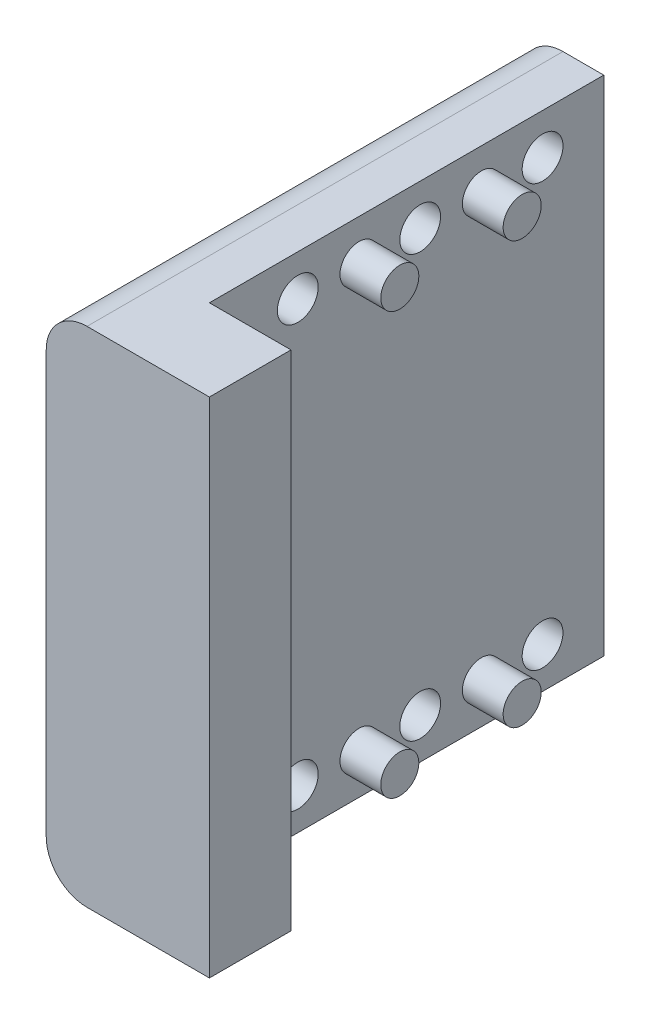
SolidWorks part; units mm, degrees
ref_plane "Front Plane" through (0, 0, 0) normal (0, 0, 1) x (1, 0, 0)
ref_plane "Top Plane" through (0, 0, 0) normal (0, 1, 0) x (1, 0, 0)
ref_plane "Right Plane" through (0, 0, 0) normal (1, 0, 0) x (0, 0, -1)
sketch "Sketch1" plane through (0, 0, 0) normal (0, 1, 0) x (1, 0, 0)
  line L0 (-15.8302, 22.3908) -> (-15.8302, -12.6092)
  line L1 (-15.8302, -12.6092) -> (-3.8302, -12.6092)
  line L2 (-3.8302, -12.6092) -> (-3.8302, -6.6092)
  line L3 (-3.8302, -6.6092) -> (-9.8302, -6.6092)
  line L4 (-9.8302, -6.6092) -> (-9.8302, 22.3908)
  line L5 (-9.8302, 22.3908) -> (-15.8302, 22.3908)
  dimension "D1" = 6
  dimension "D2" = 6
  dimension "D3" = 35
  dimension "D4" = 6
extrude "Boss-Extrude3" add sketch "Sketch1" along normal blind 37
sketch "Sketch7" plane through (0, 0, -22.3908) normal (0, 0, -1) x (-1, 0, 0)
  line L1 (12.8302, 37) -> (-5.5417, 37)
  line L2 (15.8302, 34) -> (15.8302, 3)
  line L3 (12.8302, 0) -> (-5.5417, 0)
  line L4 (-5.5417, 37) -> (-5.5417, 0)
  arc A0 (15.8302, 3) -> (12.8302, 0) centre (12.8302, 3) cw
  arc A1 (12.8302, 37) -> (15.8302, 34) centre (12.8302, 34) cw
  point P9 (15.8302, 37)
  dimension "D1" = 3
extrude "Cut-Extrude4" cut sketch "Sketch7" against normal blind 37 flip side to cut
sketch "Sketch8" plane through (-9.8302, 0, 0) normal (1, 0, 0) x (0, 0, -1)
  line L0 (-6.6092, 37) -> (-6.6092, 34) construction
  line L1 (-6.6092, 37) -> (-6.6092, 0) construction
  line L2 (-6.6092, 34) -> (-1.6092, 34) construction
  line L3 (-1.6092, 34) -> (1.3908, 34) construction
  line L4 (1.3908, 34) -> (7.3908, 34) construction
  line L5 (7.3908, 34) -> (10.3908, 34) construction
  line L6 (-6.6092, 0) -> (-6.6092, 3) construction
  line L7 (-6.6092, 37) -> (-6.6092, 0) construction
  line L8 (-6.6092, 3) -> (-1.6092, 3) construction
  line L9 (-1.6092, 3) -> (1.3908, 3) construction
  line L10 (1.3908, 3) -> (7.3908, 3) construction
  line L11 (7.3908, 3) -> (10.3908, 3) construction
  line L12 (10.3908, 34) -> (16.3908, 34) construction
  line L13 (16.3908, 34) -> (19.3908, 34) construction
  line L14 (10.3908, 3) -> (16.3908, 3) construction
  line L15 (16.3908, 3) -> (19.3908, 3) construction
  circle A0 centre (-0.1092, 34) radius 1.5
  circle A1 centre (8.8908, 34) radius 1.5
  circle A2 centre (-0.1092, 3) radius 1.5
  circle A3 centre (8.8908, 3) radius 1.5
  circle A4 centre (17.8908, 3) radius 1.5
  circle A5 centre (17.8908, 34) radius 1.5
  dimension "D1" = 3
  dimension "D2" = 5
  dimension "D3" = 3
  dimension "D4" = 6
  dimension "D5" = 3
  dimension "D6" = 3
  dimension "D7" = 5
  dimension "D8" = 3
  dimension "D9" = 6
  dimension "D10" = 3
  dimension "D11" = 6
  dimension "D12" = 3
  dimension "D13" = 6
  dimension "D14" = 3
extrude "Cut-Extrude5" cut sketch "Sketch8" against normal blind 3.5
sketch "Sketch9" plane through (0, 0, 6.6092) normal (0, 0, -1) x (-1, 0, 0)
  line L0 (6.8302, 37) -> (6.8302, 34) construction
  line L1 (3.8302, 37) -> (9.8302, 37) construction
  line L2 (6.8302, 0) -> (6.8302, 3) construction
  line L3 (3.8302, 0) -> (9.8302, 0) construction
  circle A0 centre (6.8302, 34) radius 1.5
  circle A1 centre (6.8302, 3) radius 1.5
  dimension "D3" = 3
  dimension "D4" = 3
  dimension "D1" = 3
  dimension "D2" = 3
extrude "Cut-Extrude6" cut sketch "Sketch9" against normal blind 3.5
sketch "Sketch10" plane through (-9.8302, 0, 0) normal (1, 0, 0) x (0, 0, -1)
  line L0 (-0.1092, 34) -> (8.8908, 34) construction
  line L1 (-0.1092, 3) -> (8.8908, 3) construction
  line L2 (8.8908, 34) -> (17.8908, 34) construction
  line L3 (8.8908, 3) -> (17.8908, 3) construction
  circle A0 centre (4.3908, 3) radius 1.4
  circle A1 centre (4.3908, 34) radius 1.4
  circle A2 centre (13.3908, 3) radius 1.4
  circle A3 centre (13.3908, 34) radius 1.4
  dimension "D1" = 2.8
  dimension "D2" = 2.8
  dimension "D3" = 2.8
  dimension "D4" = 2.8
extrude "Boss-Extrude4" add sketch "Sketch10" along normal blind 3
